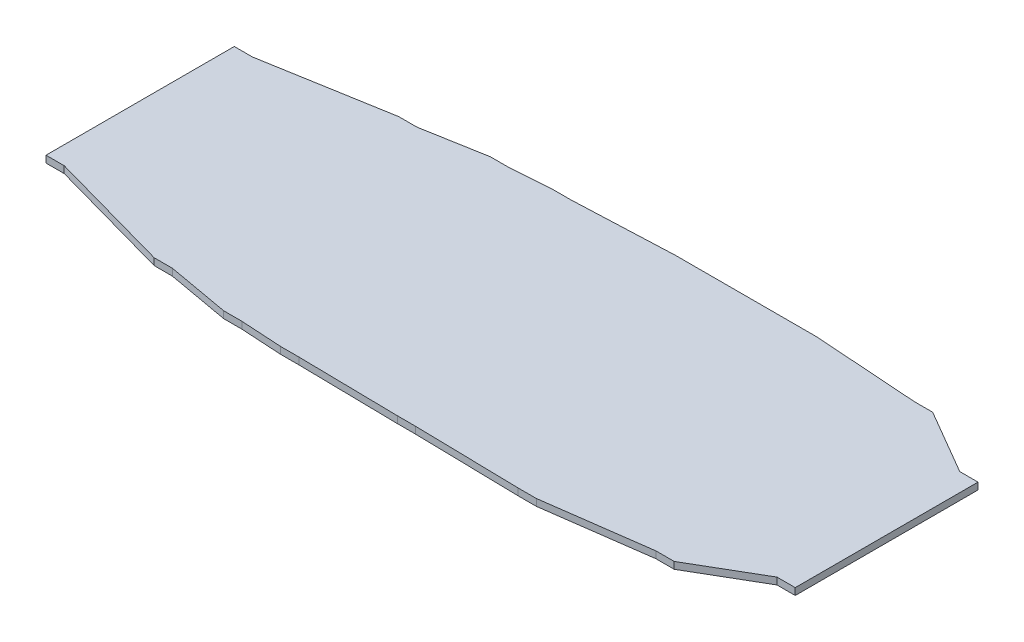
SolidWorks part; units mm, degrees
ref_plane "前视基准面" through (0, 0, 0) normal (0, 0, 1) x (1, 0, 0)
ref_plane "上视基准面" through (0, 0, 0) normal (0, 1, 0) x (1, 0, 0)
ref_plane "右视基准面" through (0, 0, 0) normal (1, 0, 0) x (0, 0, -1)
sketch "草图2" plane through (0, 0, 0) normal (0, 1, 0) x (1, 0, 0)
  line L0 (-164.2505, 43.9921) -> (-164.2505, -38.5752)
  line L1 (-164.2505, -38.5752) -> (-156.2505, -38.5752)
  line L2 (-156.2505, -38.5752) -> (-101.5936, -53.7984)
  line L3 (-101.5936, -53.7984) -> (-93.5936, -53.7984)
  line L4 (-93.5936, -53.7984) -> (-66.2085, -58.6987)
  line L5 (-66.2085, -58.6987) -> (-58.2085, -58.6987)
  line L6 (-58.2085, -58.6987) -> (-40.1412, -59.7673)
  line L7 (-40.1412, -59.7673) -> (-32.1412, -59.7673)
  line L8 (-32.1412, -59.7673) -> (11.7329, -60.4834)
  line L9 (11.7329, -60.4834) -> (19.7329, -60.4834)
  line L10 (19.7329, -60.4834) -> (65.6347, -61.4328)
  line L11 (65.6347, -61.4328) -> (73.6347, -61.4328)
  line L12 (73.6347, -61.4328) -> (119.7706, -55.106)
  line L13 (119.7706, -55.106) -> (127.7706, -55.106)
  line L14 (127.7706, -55.106) -> (156.2505, -38.5248)
  line L15 (156.2505, -38.5248) -> (164.2505, -38.5248)
  line L16 (164.2505, -38.5248) -> (164.2505, 41.6216)
  line L17 (164.2505, 41.6216) -> (156.2505, 41.6216)
  line L18 (156.2505, 41.6216) -> (127.7706, 58.2243)
  line L19 (127.7706, 58.2243) -> (119.7706, 58.2243)
  line L20 (119.7706, 58.2243) -> (73.6347, 61.4328)
  line L21 (73.6347, 61.4328) -> (65.6347, 61.4328)
  line L22 (65.6347, 61.4328) -> (19.7329, 61.4094)
  line L23 (19.7329, 61.4094) -> (11.7329, 61.4094)
  line L24 (11.7329, 61.4094) -> (-32.1412, 59.5445)
  line L25 (-32.1412, 59.5445) -> (-40.1412, 59.5445)
  line L26 (-40.1412, 59.5445) -> (-58.2085, 58.2528)
  line L27 (-58.2085, 58.2528) -> (-66.2085, 58.2528)
  line L28 (-66.2085, 58.2528) -> (-93.5936, 53.4101)
  line L29 (-93.5936, 53.4101) -> (-101.5936, 53.4101)
  line L30 (-101.5936, 53.4101) -> (-156.2505, 43.9921)
  line L31 (-156.2505, 43.9921) -> (-164.2505, 43.9921)
  dimension "D1" = 82.5673
  dimension "D2" = 80.1464
extrude "凸台-拉伸1" add sketch "草图2" along normal blind 3
